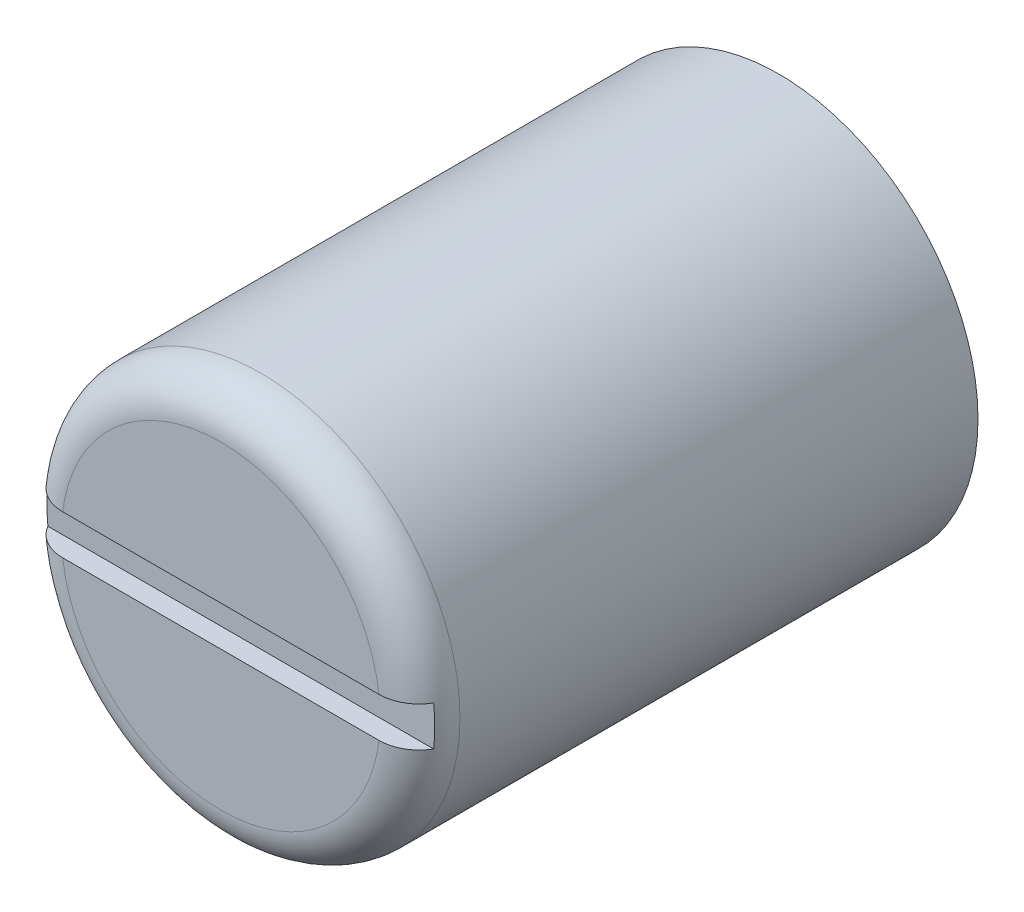
SolidWorks part; units mm, degrees
ref_plane "Front Plane" through (0, 0, 0) normal (0, 0, 1) x (1, 0, 0)
ref_plane "Top Plane" through (0, 0, 0) normal (0, 1, 0) x (1, 0, 0)
ref_plane "Right Plane" through (0, 0, 0) normal (1, 0, 0) x (0, 0, -1)
sketch "Sketch1" plane through (0, 0, 0) normal (0, 0, 1) x (1, 0, 0)
  circle A0 centre (15.442, -61.9744) radius 5
  dimension "D1" = 10
extrude "Boss-Extrude1" add sketch "Sketch1" along normal blind 14 from offset 1
sketch "Sketch2" plane through (0, 0, 15) normal (0, 0, 1) x (1, 0, 0)
  line L1 (14.367, -65.0744) -> (16.517, -65.0744)
  line L2 (14.367, -65.0744) -> (14.367, -58.8744)
  line L3 (14.367, -58.8744) -> (16.517, -58.8744)
  line L4 (16.517, -65.0744) -> (16.517, -58.8744)
  line L5 (14.367, -65.0744) -> (16.517, -58.8744) construction
  line L6 (14.367, -58.8744) -> (16.517, -65.0744) construction
  point P0 (15.442, -61.9744)
  dimension "D1" = 2.15
  dimension "D2" = 6.2
extrude "Cut-Extrude1" cut sketch "Sketch2" against normal blind 15 from offset 1.5 offset against normal yes
fillet "Fillet2" radius 1 1 edges at (20.442, -61.9744, 15)
sketch "Sketch3" plane through (0, 0, 15) normal (0, 0, 1) x (1, 0, 0)
  line L1 (10.442, -62.4744) -> (20.442, -62.4744)
  line L2 (10.442, -62.4744) -> (10.442, -61.4744)
  line L3 (10.442, -61.4744) -> (20.442, -61.4744)
  line L4 (20.442, -62.4744) -> (20.442, -61.4744)
  line L5 (10.442, -62.4744) -> (20.442, -61.4744) construction
  line L6 (10.442, -61.4744) -> (20.442, -62.4744) construction
  circle A0 centre (15.442, -61.9744) radius 2 construction
  circle A2 centre (15.442, -61.9744) radius 5 construction
  dimension "D2" = 4
  dimension "D1" = 1
extrude "Cut-Extrude2" cut sketch "Sketch3" against normal blind 0.5
